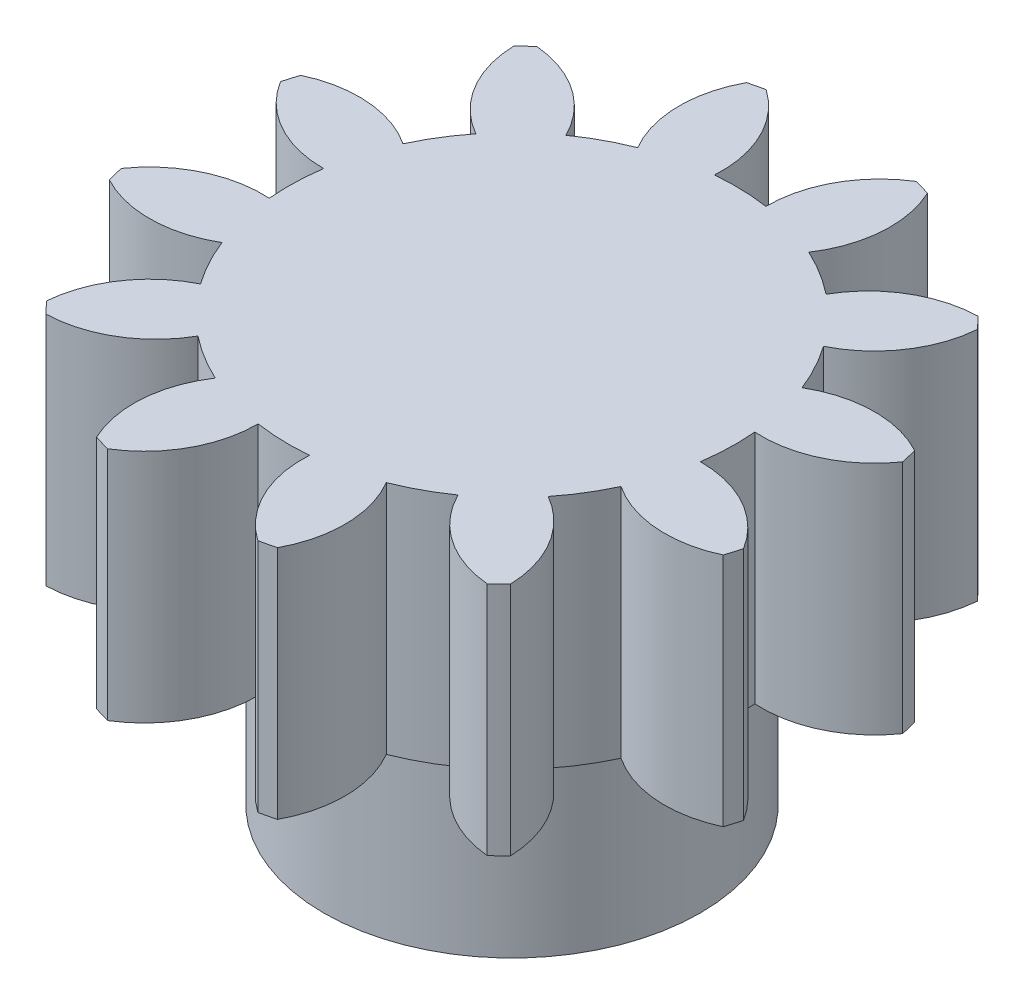
SolidWorks part; units mm, degrees
ref_plane "Front Plane" through (0, 0, 0) normal (0, 0, 1) x (1, 0, 0)
ref_plane "Top Plane" through (0, 0, 0) normal (0, 1, 0) x (1, 0, 0)
ref_plane "Right Plane" through (0, 0, 0) normal (1, 0, 0) x (0, 0, -1)
ref_plane "Plane1" through (0, -5, 0) normal (0, -1, 0) x (1, 0, 0)
sketch "Sketch1" plane through (0, -5, 0) normal (0, -1, 0) x (1, 0, 0)
  circle A0 centre (-3.8269, -0.1598) radius 4
  arc A1 (0.8524, 5.0463) -> (-1.0915, 3.7223) centre (1.0582, 2.6552) ccw
  arc A2 (-1.0915, 3.7223) -> (-2.0809, 4.2565) centre (-3.8269, -0.1598) ccw
  arc A3 (-2.0809, 4.2565) -> (-2.0398, 6.6082) centre (-4.1522, 5.4689) ccw
  arc A4 (-2.0398, 6.6082) -> (-2.3776, 6.6885) centre (-3.8269, -0.1598) ccw
  arc A5 (-2.3776, 6.6885) -> (-3.3991, 4.5699) centre (-1.0038, 4.7206) ccw
  arc A6 (-3.3991, 4.5699) -> (-4.523, 4.5379) centre (-3.8269, -0.1598) ccw
  arc A7 (-4.523, 4.5379) -> (-5.6632, 6.595) centre (-6.923, 4.5522) ccw
  arc A8 (-5.6632, 6.595) -> (-5.996, 6.4956) centre (-3.8269, -0.1598) ccw
  arc A9 (-5.996, 6.4956) -> (-5.8212, 4.1501) centre (-3.8223, 5.4783) ccw
  arc A10 (-5.8212, 4.1501) -> (-6.7786, 3.5605) centre (-3.8269, -0.1598) ccw
  arc A11 (-6.7786, 3.5605) -> (-8.7947, 4.7719) centre (-8.8642, 2.3729) ccw
  arc A12 (-8.7947, 4.7719) -> (-9.0331, 4.5195) centre (-3.8269, -0.1598) ccw
  arc A13 (-9.0331, 4.5195) -> (-7.709, 2.5756) centre (-6.642, 4.7253) ccw
  arc A14 (-7.709, 2.5756) -> (-8.2433, 1.5862) centre (-3.8269, -0.1598) ccw
  arc A15 (-8.2433, 1.5862) -> (-10.595, 1.6273) centre (-9.4557, -0.4851) ccw
  arc A16 (-10.595, 1.6273) -> (-10.6753, 1.2895) centre (-3.8269, -0.1598) ccw
  arc A17 (-10.6753, 1.2895) -> (-8.5566, 0.268) centre (-8.7074, 2.6633) ccw
  arc A18 (-8.5566, 0.268) -> (-8.5246, -0.8559) centre (-3.8269, -0.1598) ccw
  arc A19 (-8.5246, -0.8559) -> (-10.5818, -1.9961) centre (-8.539, -3.2559) ccw
  arc A20 (-10.5818, -1.9961) -> (-10.4824, -2.3289) centre (-3.8269, -0.1598) ccw
  arc A21 (-10.4824, -2.3289) -> (-8.1369, -2.1541) centre (-9.4651, -0.1552) ccw
  arc A22 (-8.1369, -2.1541) -> (-7.5472, -3.1115) centre (-3.8269, -0.1598) ccw
  arc A23 (-7.5472, -3.1115) -> (-8.7587, -5.1275) centre (-6.3597, -5.1971) ccw
  arc A24 (-8.7587, -5.1275) -> (-8.5062, -5.366) centre (-3.8269, -0.1598) ccw
  arc A25 (-8.5062, -5.366) -> (-6.5623, -4.0419) centre (-8.7121, -2.9749) ccw
  arc A26 (-6.5623, -4.0419) -> (-5.573, -4.5762) centre (-3.8269, -0.1598) ccw
  arc A27 (-5.573, -4.5762) -> (-5.6141, -6.9279) centre (-3.5017, -5.7886) ccw
  arc A28 (-5.6141, -6.9279) -> (-5.2762, -7.0082) centre (-3.8269, -0.1598) ccw
  arc A29 (-5.2762, -7.0082) -> (-4.2548, -4.8895) centre (-6.6501, -5.0403) ccw
  arc A30 (-4.2548, -4.8895) -> (-3.1309, -4.8575) centre (-3.8269, -0.1598) ccw
  arc A31 (-3.1309, -4.8575) -> (-1.9906, -6.9147) centre (-0.7309, -4.8719) ccw
  arc A32 (-1.9906, -6.9147) -> (-1.6579, -6.8153) centre (-3.8269, -0.1598) ccw
  arc A33 (-1.6579, -6.8153) -> (-1.8326, -4.4698) centre (-3.8316, -5.798) ccw
  arc A34 (-1.8326, -4.4698) -> (-0.8753, -3.8801) centre (-3.8269, -0.1598) ccw
  arc A35 (-0.8753, -3.8801) -> (1.1408, -5.0916) centre (1.2103, -2.6926) ccw
  arc A36 (1.1408, -5.0916) -> (1.3792, -4.8391) centre (-3.8269, -0.1598) ccw
  arc A37 (1.3792, -4.8391) -> (0.0552, -2.8952) centre (-1.0119, -5.045) ccw
  arc A38 (0.0552, -2.8952) -> (0.5894, -1.9059) centre (-3.8269, -0.1598) ccw
  arc A39 (0.5894, -1.9059) -> (2.9411, -1.947) centre (1.8018, 0.1654) ccw
  arc A40 (2.9411, -1.947) -> (3.0214, -1.6091) centre (-3.8269, -0.1598) ccw
  arc A41 (3.0214, -1.6091) -> (0.9027, -0.5877) centre (1.0535, -2.983) ccw
  arc A42 (0.9027, -0.5877) -> (0.8708, 0.5363) centre (-3.8269, -0.1598) ccw
  arc A43 (0.8708, 0.5363) -> (2.9279, 1.6765) centre (0.8851, 2.9362) ccw
  arc A44 (2.9279, 1.6765) -> (2.8285, 2.0092) centre (-3.8269, -0.1598) ccw
  arc A45 (2.8285, 2.0092) -> (0.483, 1.8345) centre (1.8112, -0.1645) ccw
  arc A46 (0.483, 1.8345) -> (-0.1066, 2.7918) centre (-3.8269, -0.1598) ccw
  arc A47 (-0.1066, 2.7918) -> (1.1048, 4.8079) centre (-1.2942, 4.8774) ccw
  arc A48 (1.1048, 4.8079) -> (0.8524, 5.0463) centre (-3.8269, -0.1598) ccw
extrude "Boss-Extrude1" add sketch "Sketch1" against normal blind 5
sketch "Sketch2" plane through (0, 0, 0) normal (0, 1, 0) x (1, 0, 0)
  circle A0 centre (-3.8269, 0.1598) radius 4 construction
  circle A1 centre (-3.8269, 0.1598) radius 4
extrude "Boss-Extrude2" add sketch "Sketch2" against normal blind 9
